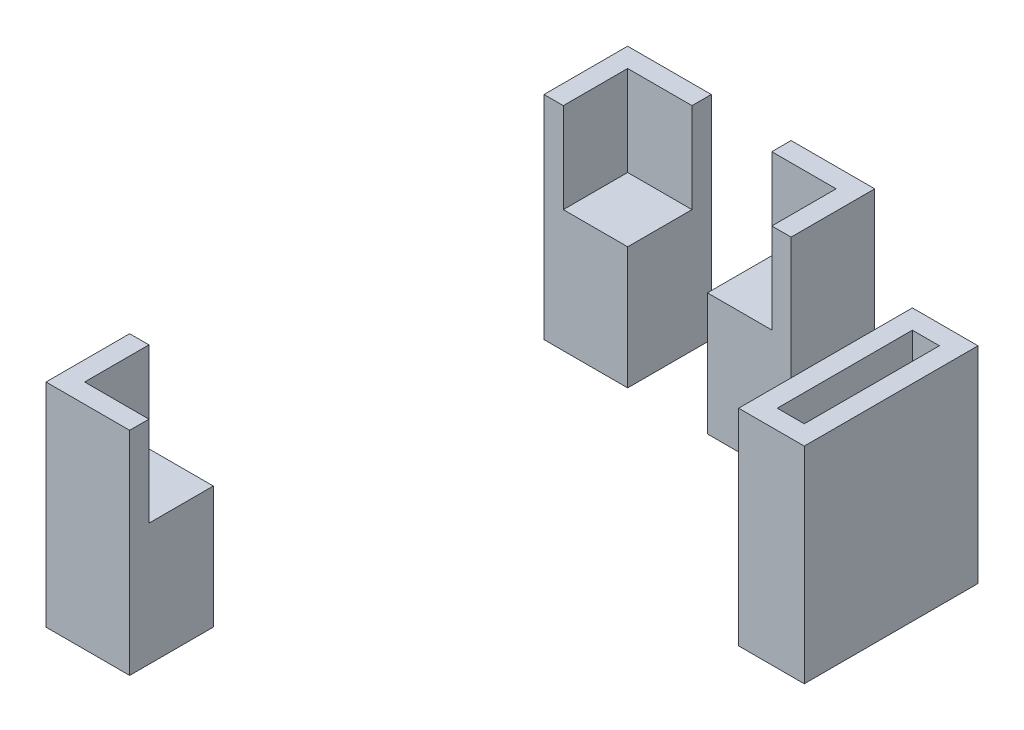
SolidWorks part; units mm, degrees
ref_plane "Front Plane" through (0, 0, 0) normal (0, 0, 1) x (1, 0, 0)
ref_plane "Top Plane" through (0, 0, 0) normal (0, 1, 0) x (1, 0, 0)
ref_plane "Right Plane" through (0, 0, 0) normal (1, 0, 0) x (0, 0, -1)
sketch "Sketch2" plane through (0, 0, 0) normal (0, 1, 0) x (1, 0, 0)
  line L0 (0, 0) -> (0, -5)
  line L1 (0, 0) -> (5, 0)
  line L2 (11.2, 0) -> (16.2, 0)
  line L3 (16.2, 0) -> (16.2, -5)
  line L4 (0, -37.2) -> (0, -42.2)
  line L5 (0, -42.2) -> (5, -42.2)
  line L6 (-1.5, 1.5) -> (5, 1.5)
  line L7 (28.175, -6.05) -> (30.275, -6.05)
  line L8 (28.175, -6.05) -> (28.175, -16.55)
  line L9 (28.175, -16.55) -> (30.275, -16.55)
  line L10 (30.275, -6.05) -> (30.275, -16.55)
  line L11 (-1.5, 1.5) -> (-1.5, -5)
  line L12 (11.2, 1.5) -> (17.7, 1.5)
  line L13 (17.7, 1.5) -> (17.7, -5)
  line L14 (-1.5, -37.2) -> (-1.5, -43.7)
  line L15 (-1.5, -43.7) -> (5, -43.7)
  line L16 (26.675, -4.55) -> (31.775, -4.55)
  line L17 (31.775, -4.55) -> (31.775, -18.05)
  line L18 (26.675, -18.05) -> (31.775, -18.05)
  line L19 (26.675, -4.55) -> (26.675, -18.05)
  line L20 (17.7, -5) -> (16.2, -5)
  line L21 (11.2, 0) -> (11.2, 1.5)
  line L22 (5, 1.5) -> (5, 0)
  line L23 (-1.5, -5) -> (0, -5)
  line L24 (-1.5, -37.2) -> (0, -37.2)
  line L25 (5, -42.2) -> (5, -43.7)
  line L26 (50, -21.7) -> (50, -43.7)
  line L27 (50, -43.7) -> (52, -43.7)
  line L28 (52, -43.7) -> (52, -21.7)
  line L29 (52, -21.7) -> (50, -21.7)
  dimension "D1" = 5
  dimension "D2" = 5
  dimension "D3" = 5
  dimension "D4" = 5
  dimension "D5" = 16.2
  dimension "D6" = 5
  dimension "D7" = 5
  dimension "D8" = 42.2
  dimension "D9" = 2.1
  dimension "D10" = 10.5
  dimension "D11" = 6.05
  dimension "D12" = 28.175
  dimension "D14" = 1.5
  dimension "D15" = 1.5
  dimension "D16" = 2
  dimension "D17" = 50
  dimension "D18" = 22
  dimension "D13" = 1.5
extrude "Boss-Extrude3" add sketch "Sketch2" along normal blind 16.5
ref_plane "Plane1" through (0, 0, 11.3) normal (0, 0, 1) x (1, 0, 0)
sketch "Sketch3" plane through (0, 0, 0) normal (0, 1, 0) x (1, 0, 0)
  line L1 (0, -5) -> (5, -5)
  line L2 (0, -5) -> (0, 0)
  line L3 (0, 0) -> (5, 0)
  line L4 (5, -5) -> (5, 0)
  line L5 (11.2, 0) -> (16.2, 0)
  line L6 (11.2, 0) -> (11.2, -5)
  line L7 (11.2, -5) -> (16.2, -5)
  line L8 (16.2, 0) -> (16.2, -5)
  line L9 (0, -37.2) -> (5, -37.2)
  line L10 (0, -37.2) -> (0, -42.2)
  line L11 (0, -42.2) -> (5, -42.2)
  line L12 (5, -37.2) -> (5, -42.2)
extrude "Boss-Extrude4" add sketch "Sketch3" along normal blind 9.5
sketch "Sketch5" plane through (0, 16.5, 0) normal (0, 1, 0) x (1, 0, 0)
  line L1 (26.675, -4.55) -> (31.775, -4.55)
  line L2 (26.675, -4.55) -> (26.675, -18.05)
  line L3 (26.675, -18.05) -> (31.775, -18.05)
  line L4 (31.775, -4.55) -> (31.775, -18.05)
extrude "Cut-Extrude1" cut sketch "Sketch5" against normal blind 0.5
sketch "Sketch4" plane through (0, 0, 0) normal (0, 1, 0) x (1, 0, 0)
  line L2 (28.175, -6.05) -> (30.275, -6.05)
  line L3 (28.175, -6.05) -> (28.175, -16.55)
  line L4 (28.175, -16.55) -> (30.275, -16.55)
  line L5 (30.275, -6.05) -> (30.275, -16.55)
extrude "Boss-Extrude5" add sketch "Sketch4" along normal offset from surface (13 mm away) 3 up to face at (29.225, 16, 11.3)
sketch "Sketch6" plane through (0, 16.5, 0) normal (0, 1, 0) x (1, 0, 0)
  line L1 (50, -21.7) -> (52, -21.7)
  line L2 (50, -21.7) -> (50, -43.7)
  line L3 (50, -43.7) -> (52, -43.7)
  line L4 (52, -21.7) -> (52, -43.7)
extrude "Cut-Extrude2" cut sketch "Sketch6" against normal through all
